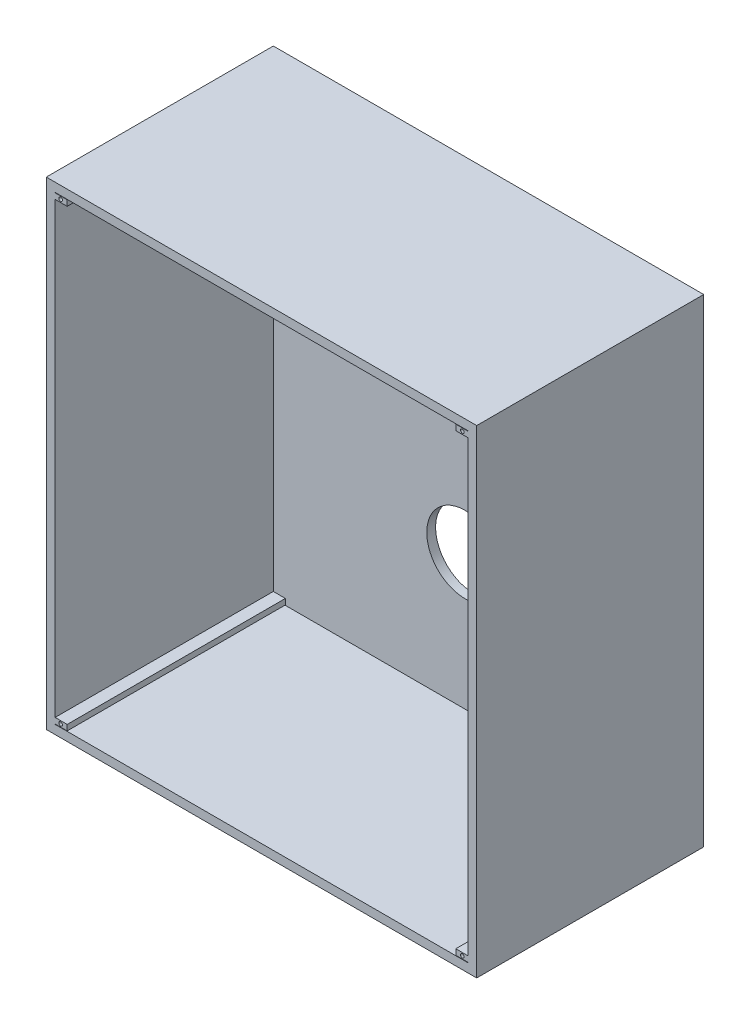
SolidWorks part; units mm, degrees
ref_plane "Front Plane" through (0, 0, 0) normal (0, 0, 1) x (1, 0, 0)
ref_plane "Top Plane" through (0, 0, 0) normal (0, 1, 0) x (1, 0, 0)
ref_plane "Right Plane" through (0, 0, 0) normal (1, 0, 0) x (0, 0, -1)
sketch "Sketch1" plane through (0, 0, 0) normal (0, 1, 0) x (1, 0, 0)
  line L1 (-61.8097, 32.6031) -> (61.8097, 32.6031)
  line L2 (-61.8097, 32.6031) -> (-61.8097, -32.6031)
  line L3 (-61.8097, -32.6031) -> (61.8097, -32.6031)
  line L4 (61.8097, 32.6031) -> (61.8097, -32.6031)
  line L5 (-61.8097, 32.6031) -> (61.8097, -32.6031) construction
  line L6 (-61.8097, -32.6031) -> (61.8097, 32.6031) construction
  point P0 (0, 0)
extrude "Boss-Extrude1" add sketch "Sketch1" along normal blind 137.414
shell "Shell1" thickness 2.54
sketch "Sketch2" plane through (0, 0, -32.6031) normal (0, 0, -1) x (-1, 0, 0)
  line L0 (-61.8097, 68.707) -> (61.8097, 68.707) construction
  line L1 (-61.8097, 137.414) -> (-61.8097, 0) construction
  line L2 (61.8097, 137.414) -> (61.8097, 0) construction
  circle A0 centre (-42.9825, 126.1517) radius 3.2166
  circle A1 centre (-17.6939, 108.2962) radius 6.6942
  circle A2 centre (4.2013, 96.4194) radius 10.9928
  circle A3 centre (4.2013, 40.9946) radius 10.9928
  circle A4 centre (-17.6939, 29.1178) radius 6.6942
  circle A5 centre (-42.9825, 11.2623) radius 3.2166
extrude "Cut-Extrude1" cut sketch "Sketch2" against normal blind 137.414
sketch "Sketch3" plane through (0, 0, -30.0631) normal (0, 0, 1) x (1, 0, 0)
  line L0 (59.2697, 134.874) -> (59.2697, 2.54) construction
  line L1 (55.8062, 134.7622) -> (59.2697, 134.7622)
  line L2 (55.8062, 134.7622) -> (55.8062, 133.1398)
  line L3 (55.8062, 133.1398) -> (59.2697, 133.1398)
  line L4 (59.2697, 134.7622) -> (59.2697, 133.1398)
  line L5 (55.8062, 134.7622) -> (59.2697, 133.1398) construction
  line L6 (55.8062, 133.1398) -> (59.2697, 134.7622) construction
  line L7 (59.2697, 68.707) -> (-59.2697, 68.707) construction
  line L8 (59.2697, 134.874) -> (59.2697, 2.54) construction
  line L9 (-59.2697, 134.874) -> (-59.2697, 2.54) construction
  line L10 (0, 134.874) -> (0, 2.54) construction
  line L11 (59.2697, 134.874) -> (-59.2697, 134.874) construction
  line L12 (-59.2697, 2.54) -> (59.2697, 2.54) construction
  line L13 (-55.8062, 133.1398) -> (-59.2697, 134.7622) construction
  line L14 (-55.8062, 134.7622) -> (-59.2697, 133.1398) construction
  line L15 (-59.2697, 134.7622) -> (-59.2697, 133.1398)
  line L16 (-55.8062, 133.1398) -> (-59.2697, 133.1398)
  line L17 (-55.8062, 134.7622) -> (-55.8062, 133.1398)
  line L18 (-55.8062, 134.7622) -> (-59.2697, 134.7622)
  line L19 (-55.8062, 2.6518) -> (-59.2697, 4.2742) construction
  line L20 (-55.8062, 4.2742) -> (-59.2697, 2.6518) construction
  line L21 (55.8062, 4.2742) -> (59.2697, 2.6518) construction
  line L22 (55.8062, 2.6518) -> (59.2697, 4.2742) construction
  line L23 (-55.8062, 2.6518) -> (-59.2697, 2.6518)
  line L24 (-55.8062, 2.6518) -> (-55.8062, 4.2742)
  line L25 (-55.8062, 4.2742) -> (-59.2697, 4.2742)
  line L26 (-59.2697, 2.6518) -> (-59.2697, 4.2742)
  line L27 (59.2697, 2.6518) -> (59.2697, 4.2742)
  line L28 (55.8062, 4.2742) -> (59.2697, 4.2742)
  line L29 (55.8062, 2.6518) -> (55.8062, 4.2742)
  line L30 (55.8062, 2.6518) -> (59.2697, 2.6518)
  point P0 (57.5379, 133.951)
  point P23 (-57.5379, 133.951)
  point P32 (-57.5379, 3.463)
  point P33 (57.5379, 3.463)
extrude "Boss-Extrude2" add sketch "Sketch3" along normal up to surface (62.6662 mm away) up to face at (0, 68.707, 32.6031)
sketch "Sketch4" plane through (0, 0, 32.6031) normal (0, 0, 1) x (1, 0, 0)
  line L0 (-61.8097, 68.707) -> (61.8097, 68.707) construction
  line L1 (-61.8097, 137.414) -> (-61.8097, 0) construction
  line L2 (61.8097, 137.414) -> (61.8097, 0) construction
  line L3 (0, 137.414) -> (0, 0) construction
  line L4 (-61.8097, 137.414) -> (61.8097, 137.414) construction
  circle A0 centre (57.6942, 133.9604) radius 0.5252
  circle A1 centre (-57.6942, 133.9604) radius 0.5252
  circle A2 centre (57.6942, 3.4536) radius 0.5252
  circle A3 centre (-57.6942, 3.4536) radius 0.5252
extrude "Cut-Extrude2" cut sketch "Sketch4" against normal blind 10.668
